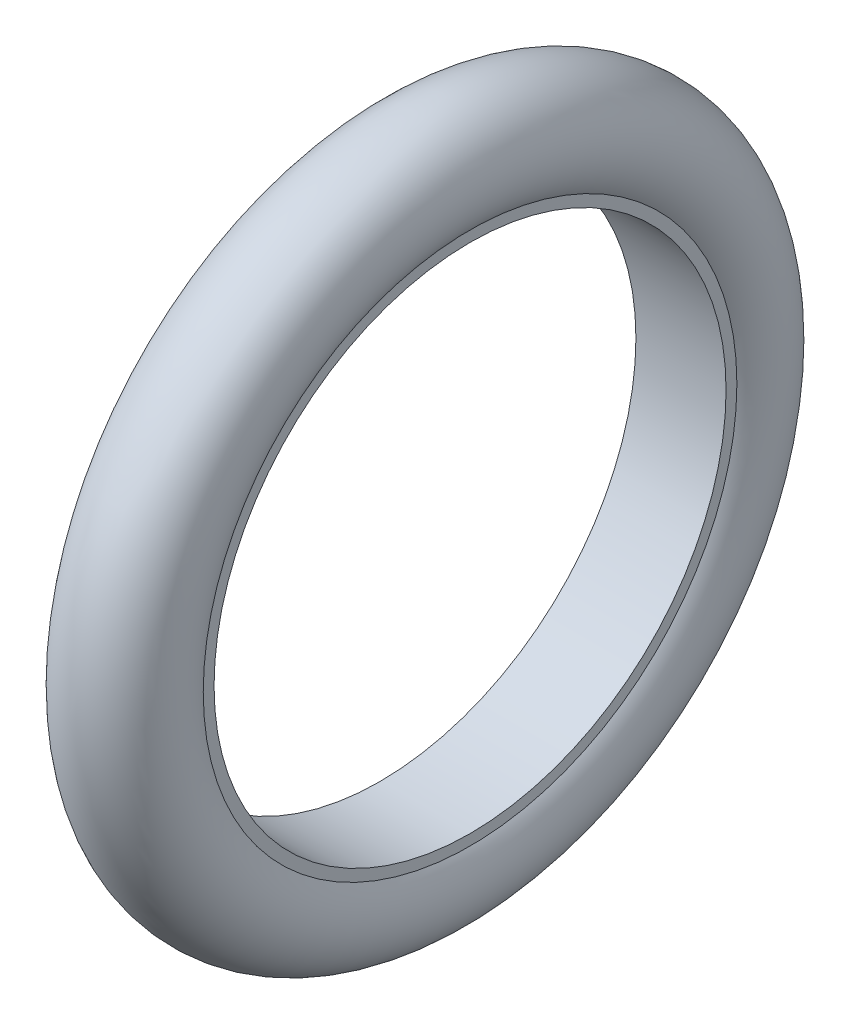
SolidWorks part; units mm, degrees
material "BUTYL"
ref_plane "Front Plane" through (0, 0, 0) normal (0, 0, 1) x (1, 0, 0)
ref_plane "Top Plane" through (0, 0, 0) normal (0, 1, 0) x (1, 0, 0)
ref_plane "Right Plane" through (0, 0, 0) normal (1, 0, 0) x (0, 0, -1)
sketch "Sketch1" plane through (0, 0, 0) normal (0, 0, 1) x (1, 0, 0)
  line L0 (-32.6305, 0) -> (36.9402, 0) construction
  line L2 (-12.5, 74) -> (-12.5, 71)
  line L3 (-12.5, 71) -> (12.5, 71)
  line L4 (12.5, 71) -> (12.5, 74)
  arc A1 (12.5, 74) -> (-12.5, 74) centre (0, 83.1652) ccw
  point P3 (0, 0)
  point P7 (0, 0)
  dimension "D3" = 148
  dimension "D4" = 31
  dimension "D1" = 25
  dimension "D2" = 3
revolve "Revolve1" add sketch "Sketch1" angle 360 about L0
